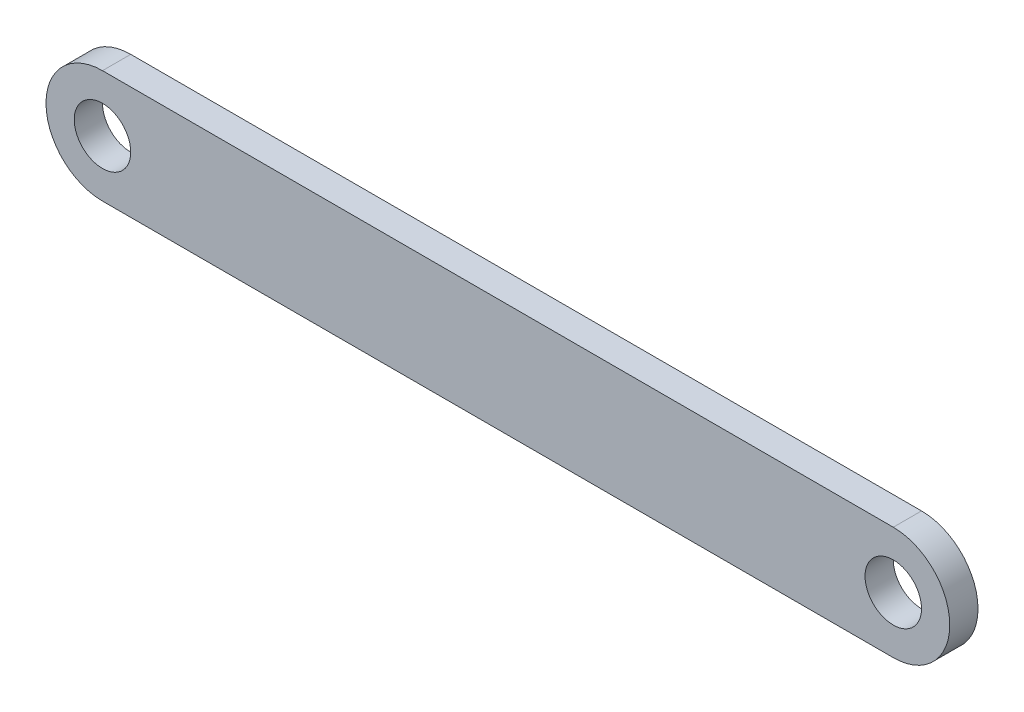
SolidWorks part; units mm, degrees
ref_plane "Alzado" through (0, 0, 0) normal (0, 0, 1) x (1, 0, 0)
ref_plane "Planta" through (0, 0, 0) normal (0, 1, 0) x (1, 0, 0)
ref_plane "Vista lateral" through (0, 0, 0) normal (1, 0, 0) x (0, 0, -1)
sketch "Croquis1" plane through (0, 0, 0) normal (0, 0, 1) x (1, 0, 0)
  line L0 (-70, 0) -> (70, 0) construction
  line L1 (-70, 10) -> (70, 10)
  line L2 (-70, -10) -> (70, -10)
  arc A0 (-70, 10) -> (-70, -10) centre (-70, 0) ccw
  arc A1 (70, -10) -> (70, 10) centre (70, 0) ccw
  circle A2 centre (70, 0) radius 5
  circle A3 centre (-70, 0) radius 5
  point P2 (0, 0)
  dimension "D2" = 10
  dimension "D1" = 140
  dimension "D3" = 20
extrude "Saliente-Extruir1" add sketch "Croquis1" along normal blind 5
